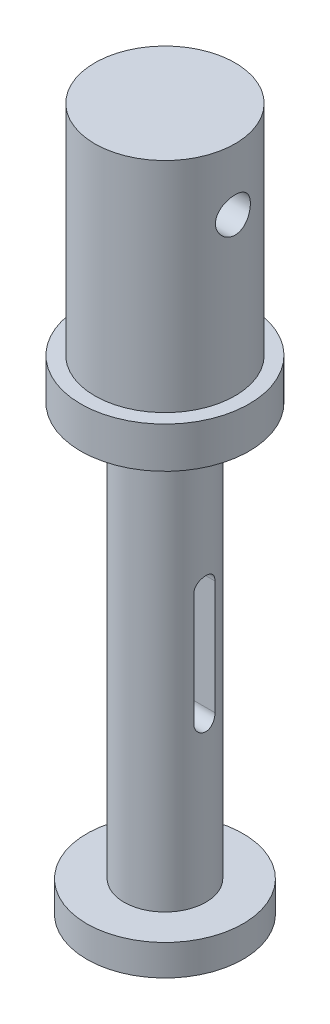
SolidWorks part; units mm, degrees
ref_plane "Front Plane" through (0, 0, 0) normal (0, 0, 1) x (1, 0, 0)
ref_plane "Top Plane" through (0, 0, 0) normal (0, 1, 0) x (1, 0, 0)
ref_plane "Right Plane" through (0, 0, 0) normal (1, 0, 0) x (0, 0, -1)
sketch "Sketch1" plane through (0, 0, 0) normal (1, 0, 0) x (0, 0, -1)
  line L0 (0, 108.3463) -> (0, -41.6537) construction
  line L1 (-75.4449, 165.5376) -> (135.2218, 165.5376) construction
  line L2 (-7.5, -41.6537) -> (7.5, -41.6537) construction
  line L3 (0, 123.6014) -> (12, 123.6014)
  line L4 (12, 123.6014) -> (12, 86.2616)
  line L5 (12, 86.2616) -> (14.3984, 86.2616)
  line L6 (14.3984, 86.2616) -> (14.3984, 79.2616)
  line L7 (6.9915, 8.7482) -> (6.9915, 79.2616)
  line L8 (6.9915, 79.2616) -> (14.3984, 79.2616)
  line L9 (6.9915, 8.7482) -> (13.3632, 8.7482)
  line L10 (13.3632, 8.7482) -> (13.3632, 3.4775)
  line L11 (13.3632, 3.4775) -> (0, 3.4775)
  line L12 (0, 123.6014) -> (0, 3.4775)
  point P8 (0, -41.6537)
  dimension "D1" = 150
  dimension "D2" = 15
  dimension "D3" = 14.3984
  dimension "D4" = 7
  dimension "D5" = 12
  dimension "D6" = 120.124
revolve "Revolve1" add sketch "Sketch1" angle 360 about L12
sketch "Sketch2" plane through (0, 0, 0) normal (1, 0, 0) x (0, 0, -1)
  line L0 (0, 123.6014) -> (0, 3.4775) construction
  circle A0 centre (0, 113.066) radius 2.9869
extrude "Cut-Extrude1" cut sketch "Sketch2" against normal through all both and the other way through all
sketch "Sketch3" plane through (0, 0, 0) normal (1, 0, 0) x (0, 0, -1)
  line L0 (0, 55.3255) -> (0, 35.8158) construction
  line L1 (1.8, 55.3255) -> (1.8, 35.8158)
  line L2 (-1.8, 55.3255) -> (-1.8, 35.8158)
  arc A0 (1.8, 55.3255) -> (-1.8, 55.3255) centre (0, 55.3255) ccw
  arc A1 (-1.8, 35.8158) -> (1.8, 35.8158) centre (0, 35.8158) ccw
  point P3 (0, 45.5707)
  dimension "D1" = 1.8
extrude "Cut-Extrude2" cut sketch "Sketch3" against normal through all both and the other way through all
sketch "Sketch4" plane through (0, 3.4775, 0) normal (0, -1, 0) x (1, 0, 0)
  circle A0 centre (0, 0) radius 13.3632 construction
  circle A1 centre (0, 0) radius 13.3632
